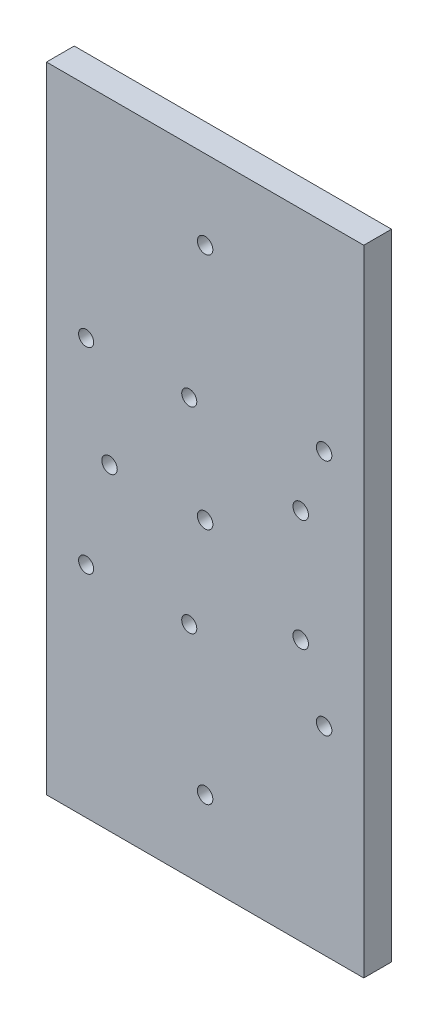
SolidWorks part; units mm, degrees
ref_plane "前视基准面" through (0, 0, 0) normal (0, 0, 1) x (1, 0, 0)
ref_plane "上视基准面" through (0, 0, 0) normal (0, 1, 0) x (1, 0, 0)
ref_plane "右视基准面" through (0, 0, 0) normal (1, 0, 0) x (0, 0, -1)
other "Configuration Table"
sketch "草图1" plane through (0, 0, 0) normal (0, 0, 1) x (1, 0, 0)
  line L0 (0, 80) -> (0, -80)
  line L1 (-40, -80) -> (40, -80)
  line L2 (-40, -80) -> (-40, 80)
  line L3 (-40, 80) -> (40, 80)
  line L4 (40, -80) -> (40, 80)
  line L5 (0, 80) -> (0, -80) construction
  line L6 (-40, 0) -> (40, 0) construction
  line L7 (30, 80) -> (30, -80)
  circle A0 centre (0, 60) radius 1.95
  circle A1 centre (0, 0) radius 1.95
  circle A2 centre (0, -60) radius 1.95
  circle A3 centre (30, 30) radius 1.95
  circle A4 centre (30, -30) radius 1.95
  point P0 (0, 0)
  dimension "D3" = 3.9
  dimension "D4" = 3.9
  dimension "D5" = 3.9
  dimension "D7" = 60
  dimension "D8" = 60
  dimension "D10" = 3.9
  dimension "D11" = 3.9
  dimension "D12" = 30
  dimension "D13" = 30
  dimension "D1" = 160
  dimension "D2" = 80
  dimension "D6" = 10
  dimension "D9" = 30
extrude "凸台-拉伸1" add sketch "草图1" along normal blind 7 contours A2 L0 A1 A0 L3 L2 L1 | A4 L7 A3 L3 L0 A0 A1 A2 L1 | A4 L7 L1 L4 L3 A3
sketch "草图3" plane through (0, 0, 7) normal (0, 0, 1) x (1, 0, 0)
  line L0 (-40, -80) -> (-40, 80) construction
  line L1 (-30, -24.75) -> (-4, -24.75)
  line L2 (-30, -24.75) -> (-30, 24.75)
  line L3 (-30, 24.75) -> (-4, 24.75)
  line L4 (-4, -24.75) -> (-4, 24.75)
  line L5 (-17, 24.75) -> (-17, -24.75) construction
  line L6 (-30, 0) -> (-4, 0) construction
  circle A0 centre (-30, 24.75) radius 1.9
  circle A1 centre (-4, 24.75) radius 1.9
  circle A2 centre (-4, -24.75) radius 1.9
  circle A3 centre (-30, -24.75) radius 1.9
  point P0 (-17, 0)
  dimension "D3" = 3.8
  dimension "D4" = 3.8
  dimension "D5" = 27.711
  dimension "D6" = 3.8
  dimension "D7" = 3.8
  dimension "D1" = 49.5
  dimension "D2" = 26
  dimension "D8" = 10
extrude "切除-拉伸2" cut sketch "草图3" against normal blind 10 contours L2 A0 L3 | L3 A0 L2 | L3 A1 L4 | L4 A1 L3 | L2 A3 L1 | L1 A3 L2 | L1 A2 L4 | L4 A2 L1
sketch "草图2" plane through (0, 0, 7) normal (0, 0, 1) x (1, 0, 0)
  line L1 (-24.1, -14.1) -> (24.1, -14.1)
  line L2 (-24.1, -14.1) -> (-24.1, 14.1)
  line L3 (-24.1, 14.1) -> (24.1, 14.1)
  line L4 (24.1, -14.1) -> (24.1, 14.1)
  line L5 (0, 14.1) -> (0, -14.1) construction
  line L6 (-24.1, 0) -> (24.1, 0) construction
  circle A1 centre (24.1, 14.1) radius 1.95
  circle A3 centre (24.1, -14.1) radius 1.95
  circle A4 centre (-24.1, 0) radius 1.95
  point P0 (0, 0)
  dimension "D3" = 3.9
  dimension "D4" = 3.9
  dimension "D6" = 3.9
  dimension "D1" = 48.2
  dimension "D2" = 28.2
extrude "切除-拉伸1" cut sketch "草图2" against normal blind 10 contours L2 A4 | L2 A4 | L4 A3 L1 | L1 A3 L4 | L4 A1 L3 | L3 A1 L4
